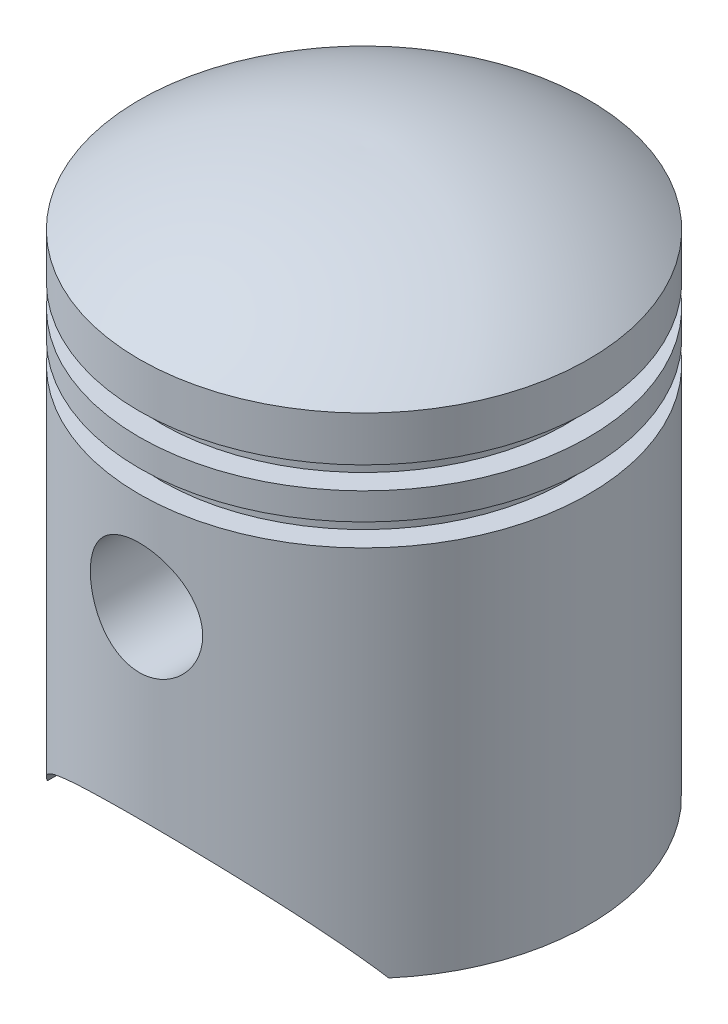
SolidWorks part; units mm, degrees
ref_plane "Front Plane" through (0, 0, 0) normal (0, 0, 1) x (1, 0, 0)
ref_plane "Top Plane" through (0, 0, 0) normal (0, 1, 0) x (1, 0, 0)
ref_plane "Right Plane" through (0, 0, 0) normal (1, 0, 0) x (0, 0, -1)
sketch "Sketch1" plane through (0, 0, 0) normal (0, 0, 1) x (1, 0, 0)
  line L0 (0, 62.5) -> (0, 60.4994)
  line L1 (23, 0) -> (25, 0)
  line L2 (25, 0) -> (25, 41.5)
  line L3 (25, 41.5) -> (22.5, 41.5)
  line L4 (22.5, 41.5) -> (22.5, 44)
  line L5 (22.5, 44) -> (25, 44)
  line L6 (25, 44) -> (25, 47)
  line L7 (25, 47) -> (22.5, 47)
  line L8 (22.5, 47) -> (22.5, 49.5)
  line L9 (22.5, 49.5) -> (25, 49.5)
  line L10 (25, 49.5) -> (25, 54.5)
  line L12 (0, 0) -> (25, 0) construction
  line L13 (23, 0) -> (23, 39.5)
  line L14 (23, 39.5) -> (20.5, 39.5)
  line L15 (20.5, 39.5) -> (20.5, 45.5)
  line L16 (20.5, 45.5) -> (20.5, 45.5)
  line L17 (20.5, 45.5) -> (20.5, 45.5)
  line L18 (20.5, 45.5) -> (20.5, 45.5)
  line L19 (20.5, 45.5) -> (20.5, 51.5)
  line L20 (20.5, 51.5) -> (23, 51.5)
  line L21 (23, 51.5) -> (23, 53.4845)
  line L22 (23, 2) -> (23, 39.5) construction
  line L23 (2, 60.4985) -> (2, 2) construction
  line L24 (2, 2) -> (23, 2) construction
  line L25 (0, 62.5) -> (0, 0) construction
  arc A0 (0, 62.5) -> (25, 54.5) centre (0.9839, 22.5121) cw
  arc A1 (0, 60.4994) -> (23, 53.4845) centre (0.9839, 22.5121) cw
  arc A2 (2, 60.4985) -> (23, 53.4845) centre (0.9839, 22.5121) cw construction
  dimension "D9" = 40
  dimension "D3" = 41.5
  dimension "D4" = 2.5
  dimension "D5" = 2.5
  dimension "D6" = 3
  dimension "D7" = 5
  dimension "D8" = 2.5
  dimension "D10" = 2
revolve "Revolve1" add sketch "Sketch1" angle 360 about L0
sketch "Sketch2" plane through (0, 0, 0) normal (0, 0, 1) x (1, 0, 0)
  line L0 (19, 0) -> (-19, 0)
  line L1 (-25, 0) -> (25, 0) construction
  line L2 (0, 0) -> (0, 10) construction
  arc A0 (-19, 0) -> (19, 0) centre (0, -12.6052) cw
  dimension "D1" = 10
  dimension "D2" = 38
extrude "Cut-Extrude1" cut sketch "Sketch2" against normal mid plane 70
sketch "Sketch4" plane through (0, 0, 0) normal (0, 0, 1) x (1, 0, 0)
  line L0 (0, 62.5629) -> (0, 30.5629) construction
  circle A0 centre (0, 30.5629) radius 6.25
  dimension "D2" = 12.5
  dimension "D1" = 32
extrude "Cut-Extrude2" cut sketch "Sketch4" against normal mid plane 80
ref_plane "Plane1" through (0, 0, 12) normal (0, 0, 1) x (1, 0, 0)
sketch "Sketch6" plane through (0, 0, 12) normal (0, 0, 1) x (1, 0, 0)
  circle A0 centre (0, 30.5629) radius 6.25 construction
  circle A1 centre (0, 30.5629) radius 6.25
  circle A2 centre (0, 30.5629) radius 7.25
  dimension "D1" = 14.5
extrude "Boss-Extrude1" add sketch "Sketch6" along normal up to next
mirror "Mirror2" about plane through (0, 0, 0) normal (0, 0, 1) of "Boss-Extrude1"
